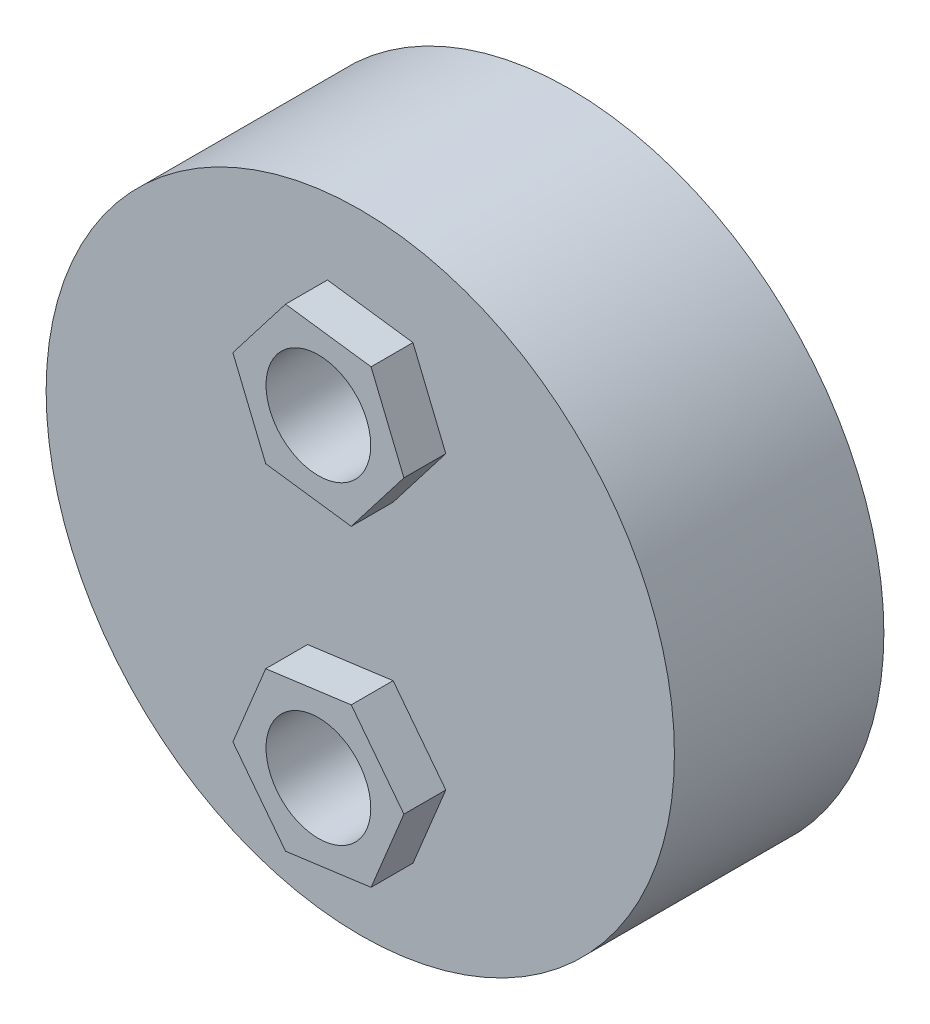
SolidWorks part; units mm, degrees
ref_plane "Front" through (0, 0, 0) normal (0, 0, 1) x (1, 0, 0)
ref_plane "Top" through (0, 0, 0) normal (0, 1, 0) x (1, 0, 0)
ref_plane "Right" through (0, 0, 0) normal (1, 0, 0) x (0, 0, -1)
sketch "Çizim1" plane through (0, 0, 0) normal (0, 0, 1) x (1, 0, 0)
  circle A0 centre (0, 0) radius 15
extrude "Yükseklik-Ekstrüzyon1" add sketch "Çizim1" along normal blind 10
sketch "Çizim2" plane through (0, 0, 10) normal (0, 0, 1) x (1, 0, 0)
  line L0 (0, 15) -> (0, 7.5)
  line L1 (-15, 0) -> (15, 0)
  circle A0 centre (0, 0) radius 15 construction
  circle A1 centre (0, 7.5) radius 2.5
  circle A2 centre (0, -7.5) radius 2.5
extrude "Kes-Ekstrüzyon1" cut sketch "Çizim2" against normal blind 5
sketch "Çizim3" plane through (0, 0, 10) normal (0, 0, 1) x (1, 0, 0)
  line L0 (-15, 0) -> (15, 0)
  line L1 (1.5676, 3.6904) -> (4.083, 6.9527)
  line L2 (4.083, 6.9527) -> (2.5155, 10.7624)
  line L3 (2.5155, 10.7624) -> (-1.5676, 11.3096)
  line L4 (-1.5676, 11.3096) -> (-4.083, 8.0473)
  line L5 (-4.083, 8.0473) -> (-2.5155, 4.2376)
  line L6 (-2.5155, 4.2376) -> (1.5676, 3.6904)
  line L7 (-2.5155, -4.2376) -> (1.5676, -3.6904)
  line L8 (-4.083, -8.0473) -> (-2.5155, -4.2376)
  line L9 (-1.5676, -11.3096) -> (-4.083, -8.0473)
  line L10 (2.5155, -10.7624) -> (-1.5676, -11.3096)
  line L11 (4.083, -6.9527) -> (2.5155, -10.7624)
  line L12 (1.5676, -3.6904) -> (4.083, -6.9527)
  circle A0 centre (0, 7.5) radius 3.5676 construction
  circle A1 centre (0, 0) radius 15 construction
  circle A2 centre (0, -7.5) radius 3.5676 construction
  circle M2 centre (0, -7.5) radius 2.5
  circle M3 centre (0, 7.5) radius 2.5
extrude "Yükseklik-Ekstrüzyon3" add sketch "Çizim3" along normal blind 2 contours L5 L6 L1 L2 L3 L4 M3 | L12 L7 L8 L9 L10 L11 M2
